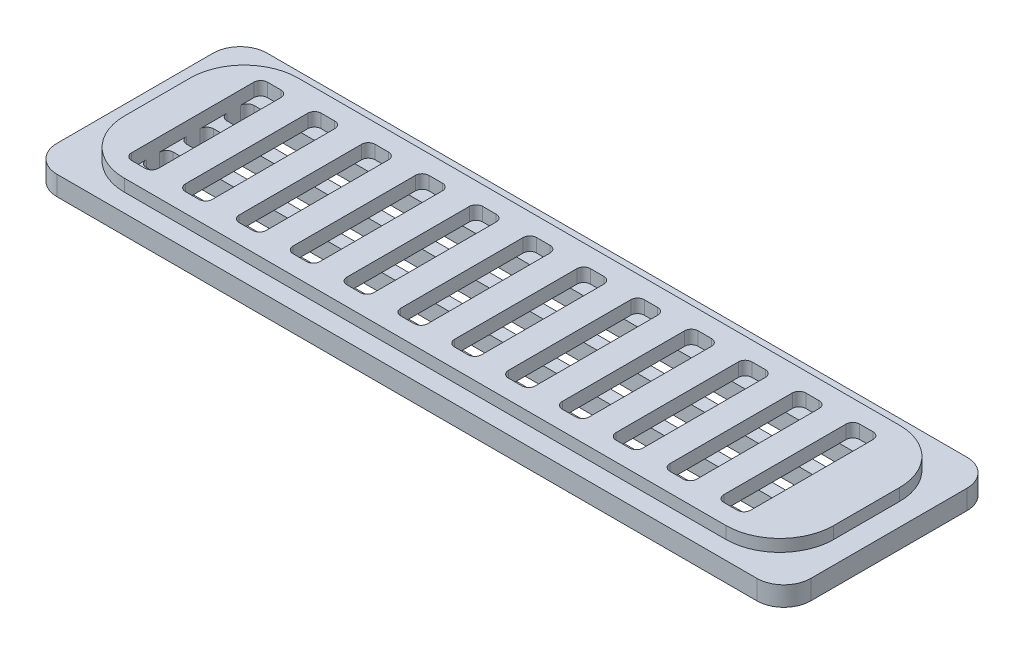
SolidWorks part; units mm, degrees
ref_plane "Front Plane" through (0, 0, 0) normal (0, 0, 1) x (1, 0, 0)
ref_plane "Top Plane" through (0, 0, 0) normal (0, 1, 0) x (1, 0, 0)
ref_plane "Right Plane" through (0, 0, 0) normal (1, 0, 0) x (0, 0, -1)
sketch "Sketch1" plane through (0, 0, 0) normal (0, 1, 0) x (1, 0, 0)
  line L1 (-26, -7.8) -> (26, -7.8)
  line L2 (-28, -5.8) -> (-28, 5.8)
  line L3 (-26, 7.8) -> (26, 7.8)
  line L4 (28, -5.8) -> (28, 5.8)
  line L5 (-28, -7.8) -> (28, 7.8) construction
  line L6 (-28, 7.8) -> (28, -7.8) construction
  arc A0 (26, 7.8) -> (28, 5.8) centre (26, 5.8) cw
  arc A1 (26, -7.8) -> (28, -5.8) centre (26, -5.8) ccw
  arc A2 (-26, -7.8) -> (-28, -5.8) centre (-26, -5.8) cw
  arc A3 (-28, 5.8) -> (-26, 7.8) centre (-26, 5.8) cw
  point P0 (0, 0)
  dimension "D3" = 2
  dimension "D1" = 56
  dimension "D2" = 15.6
extrude "Boss-Extrude1" add sketch "Sketch1" along normal blind 1.45
sketch "Sketch2" plane through (0, 1.45, 0) normal (0, 1, 0) x (1, 0, 0)
  line L1 (-22.35, -6.45) -> (22.35, -6.45)
  line L2 (-26.35, -2.45) -> (-26.35, 2.45)
  line L3 (-22.35, 6.45) -> (22.35, 6.45)
  line L4 (26.35, -2.45) -> (26.35, 2.45)
  line L5 (-26.35, -6.45) -> (26.35, 6.45) construction
  line L6 (-26.35, 6.45) -> (26.35, -6.45) construction
  arc A0 (22.35, -6.45) -> (26.35, -2.45) centre (22.35, -2.45) ccw
  arc A1 (22.35, 6.45) -> (26.35, 2.45) centre (22.35, 2.45) cw
  arc A2 (-22.35, -6.45) -> (-26.35, -2.45) centre (-22.35, -2.45) cw
  arc A3 (-26.35, 2.45) -> (-22.35, 6.45) centre (-22.35, 2.45) cw
  point P0 (0, 0)
  dimension "D3" = 4
  dimension "D1" = 52.7
  dimension "D2" = 12.9
extrude "Boss-Extrude2" add sketch "Sketch2" along normal blind 0.9
sketch "Sketch3" plane through (0, 2.35, 0) normal (0, 1, 0) x (1, 0, 0)
  line L0 (35.4623, 0) -> (-35.0934, 0) construction
  line L1 (-23.2199, 5.0461) -> (-22.2199, 5.0461)
  line L2 (-23.7199, 4.5461) -> (-23.7199, -4.5461)
  line L3 (-23.2199, -5.0461) -> (-22.2199, -5.0461)
  line L4 (-21.7199, 4.5461) -> (-21.7199, -4.5461)
  line L5 (-23.7199, 5.0461) -> (-21.7199, -5.0461) construction
  line L6 (-23.7199, -5.0461) -> (-21.7199, 5.0461) construction
  line L7 (22.35, 6.45) -> (-22.35, 6.45) construction
  line L8 (-26.35, 2.45) -> (-26.35, -2.45) construction
  line L9 (-19.2199, 5.0461) -> (-18.2199, 5.0461)
  line L10 (-19.7199, 4.5461) -> (-19.7199, -4.5461)
  line L11 (-19.2199, -5.0461) -> (-18.2199, -5.0461)
  line L12 (-17.7199, 4.5461) -> (-17.7199, -4.5461)
  line L13 (-19.7199, 5.0461) -> (-17.7199, -5.0461) construction
  line L14 (-19.7199, -5.0461) -> (-17.7199, 5.0461) construction
  line L15 (-15.2199, 5.0461) -> (-14.2199, 5.0461)
  line L16 (-15.7199, 4.5461) -> (-15.7199, -4.5461)
  line L17 (-15.2199, -5.0461) -> (-14.2199, -5.0461)
  line L18 (-13.7199, 4.5461) -> (-13.7199, -4.5461)
  line L19 (-15.7199, 5.0461) -> (-13.7199, -5.0461) construction
  line L20 (-15.7199, -5.0461) -> (-13.7199, 5.0461) construction
  line L21 (-11.2199, 5.0461) -> (-10.2199, 5.0461)
  line L22 (-11.7199, 4.5461) -> (-11.7199, -4.5461)
  line L23 (-11.2199, -5.0461) -> (-10.2199, -5.0461)
  line L24 (-9.7199, 4.5461) -> (-9.7199, -4.5461)
  line L25 (-11.7199, 5.0461) -> (-9.7199, -5.0461) construction
  line L26 (-11.7199, -5.0461) -> (-9.7199, 5.0461) construction
  line L27 (-7.2199, 5.0461) -> (-6.2199, 5.0461)
  line L28 (-7.7199, 4.5461) -> (-7.7199, -4.5461)
  line L29 (-7.2199, -5.0461) -> (-6.2199, -5.0461)
  line L30 (-5.7199, 4.5461) -> (-5.7199, -4.5461)
  line L31 (-7.7199, 5.0461) -> (-5.7199, -5.0461) construction
  line L32 (-7.7199, -5.0461) -> (-5.7199, 5.0461) construction
  line L33 (-3.2199, 5.0461) -> (-2.2199, 5.0461)
  line L34 (-3.7199, 4.5461) -> (-3.7199, -4.5461)
  line L35 (-3.2199, -5.0461) -> (-2.2199, -5.0461)
  line L36 (-1.7199, 4.5461) -> (-1.7199, -4.5461)
  line L37 (-3.7199, 5.0461) -> (-1.7199, -5.0461) construction
  line L38 (-3.7199, -5.0461) -> (-1.7199, 5.0461) construction
  line L39 (0.7801, 5.0461) -> (1.7801, 5.0461)
  line L40 (0.2801, 4.5461) -> (0.2801, -4.5461)
  line L41 (0.7801, -5.0461) -> (1.7801, -5.0461)
  line L42 (2.2801, 4.5461) -> (2.2801, -4.5461)
  line L43 (0.2801, 5.0461) -> (2.2801, -5.0461) construction
  line L44 (0.2801, -5.0461) -> (2.2801, 5.0461) construction
  line L45 (4.7801, 5.0461) -> (5.7801, 5.0461)
  line L46 (4.2801, 4.5461) -> (4.2801, -4.5461)
  line L47 (4.7801, -5.0461) -> (5.7801, -5.0461)
  line L48 (6.2801, 4.5461) -> (6.2801, -4.5461)
  line L49 (4.2801, 5.0461) -> (6.2801, -5.0461) construction
  line L50 (4.2801, -5.0461) -> (6.2801, 5.0461) construction
  line L51 (8.7801, 5.0461) -> (9.7801, 5.0461)
  line L52 (8.2801, 4.5461) -> (8.2801, -4.5461)
  line L53 (8.7801, -5.0461) -> (9.7801, -5.0461)
  line L54 (10.2801, 4.5461) -> (10.2801, -4.5461)
  line L55 (8.2801, 5.0461) -> (10.2801, -5.0461) construction
  line L56 (8.2801, -5.0461) -> (10.2801, 5.0461) construction
  line L57 (12.7801, 5.0461) -> (13.7801, 5.0461)
  line L58 (12.2801, 4.5461) -> (12.2801, -4.5461)
  line L59 (12.7801, -5.0461) -> (13.7801, -5.0461)
  line L60 (14.2801, 4.5461) -> (14.2801, -4.5461)
  line L61 (12.2801, 5.0461) -> (14.2801, -5.0461) construction
  line L62 (12.2801, -5.0461) -> (14.2801, 5.0461) construction
  line L63 (16.7801, 5.0461) -> (17.7801, 5.0461)
  line L64 (16.2801, 4.5461) -> (16.2801, -4.5461)
  line L65 (16.7801, -5.0461) -> (17.7801, -5.0461)
  line L66 (18.2801, 4.5461) -> (18.2801, -4.5461)
  line L67 (16.2801, 5.0461) -> (18.2801, -5.0461) construction
  line L68 (16.2801, -5.0461) -> (18.2801, 5.0461) construction
  line L69 (20.7801, 5.0461) -> (21.7801, 5.0461)
  line L70 (20.2801, 4.5461) -> (20.2801, -4.5461)
  line L71 (20.7801, -5.0461) -> (21.7801, -5.0461)
  line L72 (22.2801, 4.5461) -> (22.2801, -4.5461)
  line L73 (20.2801, 5.0461) -> (22.2801, -5.0461) construction
  line L74 (20.2801, -5.0461) -> (22.2801, 5.0461) construction
  arc A0 (-23.7199, -4.5461) -> (-23.2199, -5.0461) centre (-23.2199, -4.5461) ccw
  arc A1 (-22.2199, -5.0461) -> (-21.7199, -4.5461) centre (-22.2199, -4.5461) ccw
  arc A2 (-22.2199, 5.0461) -> (-21.7199, 4.5461) centre (-22.2199, 4.5461) cw
  arc A3 (-23.2199, 5.0461) -> (-23.7199, 4.5461) centre (-23.2199, 4.5461) ccw
  arc A4 (-19.7199, -4.5461) -> (-19.2199, -5.0461) centre (-19.2199, -4.5461) ccw
  arc A5 (-18.2199, -5.0461) -> (-17.7199, -4.5461) centre (-18.2199, -4.5461) ccw
  arc A6 (-18.2199, 5.0461) -> (-17.7199, 4.5461) centre (-18.2199, 4.5461) cw
  arc A7 (-19.2199, 5.0461) -> (-19.7199, 4.5461) centre (-19.2199, 4.5461) ccw
  arc A8 (-15.7199, -4.5461) -> (-15.2199, -5.0461) centre (-15.2199, -4.5461) ccw
  arc A9 (-14.2199, -5.0461) -> (-13.7199, -4.5461) centre (-14.2199, -4.5461) ccw
  arc A10 (-14.2199, 5.0461) -> (-13.7199, 4.5461) centre (-14.2199, 4.5461) cw
  arc A11 (-15.2199, 5.0461) -> (-15.7199, 4.5461) centre (-15.2199, 4.5461) ccw
  arc A12 (-11.7199, -4.5461) -> (-11.2199, -5.0461) centre (-11.2199, -4.5461) ccw
  arc A13 (-10.2199, -5.0461) -> (-9.7199, -4.5461) centre (-10.2199, -4.5461) ccw
  arc A14 (-10.2199, 5.0461) -> (-9.7199, 4.5461) centre (-10.2199, 4.5461) cw
  arc A15 (-11.2199, 5.0461) -> (-11.7199, 4.5461) centre (-11.2199, 4.5461) ccw
  arc A16 (-7.7199, -4.5461) -> (-7.2199, -5.0461) centre (-7.2199, -4.5461) ccw
  arc A17 (-6.2199, -5.0461) -> (-5.7199, -4.5461) centre (-6.2199, -4.5461) ccw
  arc A18 (-6.2199, 5.0461) -> (-5.7199, 4.5461) centre (-6.2199, 4.5461) cw
  arc A19 (-7.2199, 5.0461) -> (-7.7199, 4.5461) centre (-7.2199, 4.5461) ccw
  arc A20 (-3.7199, -4.5461) -> (-3.2199, -5.0461) centre (-3.2199, -4.5461) ccw
  arc A21 (-2.2199, -5.0461) -> (-1.7199, -4.5461) centre (-2.2199, -4.5461) ccw
  arc A22 (-2.2199, 5.0461) -> (-1.7199, 4.5461) centre (-2.2199, 4.5461) cw
  arc A23 (-3.2199, 5.0461) -> (-3.7199, 4.5461) centre (-3.2199, 4.5461) ccw
  arc A24 (0.2801, -4.5461) -> (0.7801, -5.0461) centre (0.7801, -4.5461) ccw
  arc A25 (1.7801, -5.0461) -> (2.2801, -4.5461) centre (1.7801, -4.5461) ccw
  arc A26 (1.7801, 5.0461) -> (2.2801, 4.5461) centre (1.7801, 4.5461) cw
  arc A27 (0.7801, 5.0461) -> (0.2801, 4.5461) centre (0.7801, 4.5461) ccw
  arc A28 (4.2801, -4.5461) -> (4.7801, -5.0461) centre (4.7801, -4.5461) ccw
  arc A29 (5.7801, -5.0461) -> (6.2801, -4.5461) centre (5.7801, -4.5461) ccw
  arc A30 (5.7801, 5.0461) -> (6.2801, 4.5461) centre (5.7801, 4.5461) cw
  arc A31 (4.7801, 5.0461) -> (4.2801, 4.5461) centre (4.7801, 4.5461) ccw
  arc A32 (8.2801, -4.5461) -> (8.7801, -5.0461) centre (8.7801, -4.5461) ccw
  arc A33 (9.7801, -5.0461) -> (10.2801, -4.5461) centre (9.7801, -4.5461) ccw
  arc A34 (9.7801, 5.0461) -> (10.2801, 4.5461) centre (9.7801, 4.5461) cw
  arc A35 (8.7801, 5.0461) -> (8.2801, 4.5461) centre (8.7801, 4.5461) ccw
  arc A36 (12.2801, -4.5461) -> (12.7801, -5.0461) centre (12.7801, -4.5461) ccw
  arc A37 (13.7801, -5.0461) -> (14.2801, -4.5461) centre (13.7801, -4.5461) ccw
  arc A38 (13.7801, 5.0461) -> (14.2801, 4.5461) centre (13.7801, 4.5461) cw
  arc A39 (12.7801, 5.0461) -> (12.2801, 4.5461) centre (12.7801, 4.5461) ccw
  arc A40 (16.2801, -4.5461) -> (16.7801, -5.0461) centre (16.7801, -4.5461) ccw
  arc A41 (17.7801, -5.0461) -> (18.2801, -4.5461) centre (17.7801, -4.5461) ccw
  arc A42 (17.7801, 5.0461) -> (18.2801, 4.5461) centre (17.7801, 4.5461) cw
  arc A43 (16.7801, 5.0461) -> (16.2801, 4.5461) centre (16.7801, 4.5461) ccw
  arc A44 (20.2801, -4.5461) -> (20.7801, -5.0461) centre (20.7801, -4.5461) ccw
  arc A45 (21.7801, -5.0461) -> (22.2801, -4.5461) centre (21.7801, -4.5461) ccw
  arc A46 (21.7801, 5.0461) -> (22.2801, 4.5461) centre (21.7801, 4.5461) cw
  arc A47 (20.7801, 5.0461) -> (20.2801, 4.5461) centre (20.7801, 4.5461) ccw
  point P0 (-22.7199, 0)
  point P26 (-18.7199, 0)
  point P43 (-14.7199, 0)
  point P60 (-10.7199, 0)
  point P77 (-6.7199, 0)
  point P94 (-2.7199, 0)
  point P111 (1.2801, 0)
  point P128 (5.2801, 0)
  point P145 (9.2801, 0)
  point P162 (13.2801, 0)
  point P179 (17.2801, 0)
  point P196 (21.2801, 0)
  dimension "D4" = 0.5
  dimension "D1" = 1.4039
  dimension "D2" = 2.6301
  dimension "D3" = 2
  dimension "D5" = 12
extrude "Cut-Extrude1" cut sketch "Sketch3" against normal blind 1
sketch "Sketch4" plane through (0, 1.35, 0) normal (0, 1, 0) x (1, 0, 0)
  line L0 (-23.7199, 4.5461) -> (-23.7199, -4.5461) construction
  line L1 (-23.2199, 4.0461) -> (21.7801, 4.0461)
  line L2 (-23.7199, 3.5461) -> (-23.7199, 2.5461)
  line L3 (-23.2199, 2.0461) -> (21.7801, 2.0461)
  line L4 (22.2801, 3.5461) -> (22.2801, 2.5461)
  line L5 (22.2801, -4.5461) -> (22.2801, 4.5461) construction
  line L6 (-22.2199, 5.0461) -> (-23.2199, 5.0461) construction
  line L7 (-23.2199, 1.0461) -> (21.7801, 1.0461)
  line L8 (-23.7199, 0.5461) -> (-23.7199, -0.4539)
  line L9 (-23.2199, -0.9539) -> (21.7801, -0.9539)
  line L10 (22.2801, 0.5461) -> (22.2801, -0.4539)
  line L11 (-23.2199, -1.9539) -> (21.7801, -1.9539)
  line L12 (-23.7199, -2.4539) -> (-23.7199, -3.4539)
  line L13 (-23.2199, -3.9539) -> (21.7801, -3.9539)
  line L14 (22.2801, -2.4539) -> (22.2801, -3.4539)
  arc A0 (21.7801, -3.9539) -> (22.2801, -3.4539) centre (21.7801, -3.4539) ccw
  arc A1 (21.7801, -1.9539) -> (22.2801, -2.4539) centre (21.7801, -2.4539) cw
  arc A2 (21.7801, -0.9539) -> (22.2801, -0.4539) centre (21.7801, -0.4539) ccw
  arc A3 (21.7801, 1.0461) -> (22.2801, 0.5461) centre (21.7801, 0.5461) cw
  arc A4 (21.7801, 2.0461) -> (22.2801, 2.5461) centre (21.7801, 2.5461) ccw
  arc A5 (21.7801, 4.0461) -> (22.2801, 3.5461) centre (21.7801, 3.5461) cw
  arc A6 (-23.7199, -3.4539) -> (-23.2199, -3.9539) centre (-23.2199, -3.4539) ccw
  arc A7 (-23.2199, -1.9539) -> (-23.7199, -2.4539) centre (-23.2199, -2.4539) ccw
  arc A8 (-23.7199, -0.4539) -> (-23.2199, -0.9539) centre (-23.2199, -0.4539) ccw
  arc A9 (-23.2199, 1.0461) -> (-23.7199, 0.5461) centre (-23.2199, 0.5461) ccw
  arc A10 (-23.7199, 2.5461) -> (-23.2199, 2.0461) centre (-23.2199, 2.5461) ccw
  arc A11 (-23.2199, 4.0461) -> (-23.7199, 3.5461) centre (-23.2199, 3.5461) ccw
  point P28 (22.2801, 2.0461)
  point P41 (-23.7199, 2.0461)
  point P44 (-23.7199, 4.0461)
  dimension "D4" = 0.5
  dimension "D1" = 1
  dimension "D2" = 2
  dimension "D3" = 3
extrude "Cut-Extrude2" cut sketch "Sketch4" against normal up to next
